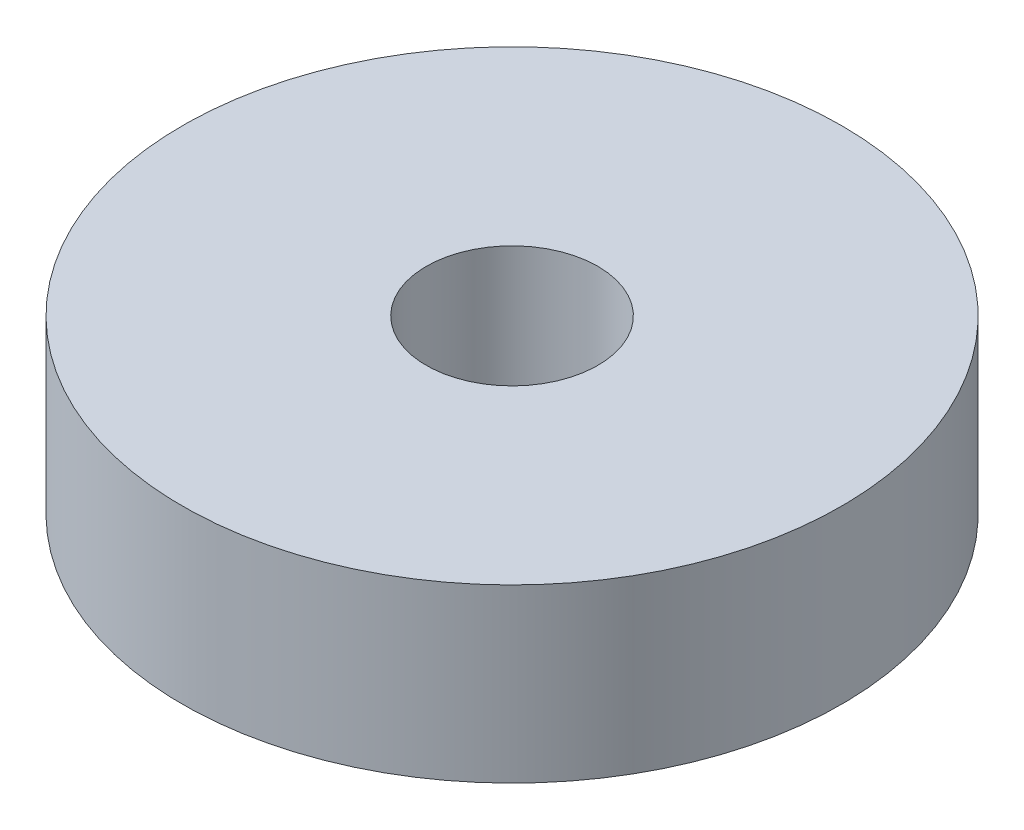
SolidWorks part; units mm, degrees
material "Ductile Iron"
ref_plane "Front Plane" through (0, 0, 0) normal (0, 0, 1) x (1, 0, 0)
ref_plane "Top Plane" through (0, 0, 0) normal (0, 1, 0) x (1, 0, 0)
ref_plane "Right Plane" through (0, 0, 0) normal (1, 0, 0) x (0, 0, -1)
sketch "Sketch1" plane through (0, 0, 0) normal (0, 0, 1) x (1, 0, 0)
  line L0 (0, 0) -> (0, 7801.7781) construction
  line L1 (0, 0) -> (7801.7781, 0) construction
  line L3 (6.096, 1.5875) -> (1.5875, 1.5875)
  line L4 (6.096, 1.5875) -> (6.096, -1.5875)
  line L5 (6.096, -1.5875) -> (1.5875, -1.5875)
  line L6 (1.5875, 1.5875) -> (1.5875, -1.5875)
  line L7 (6.096, 1.5875) -> (1.5875, -1.5875) construction
  line L8 (6.096, -1.5875) -> (1.5875, 1.5875) construction
  point P5 (3.8417, 0)
  dimension "D1" = 6.096
  dimension "D2" = 3.175
  dimension "D3" = 1.5875
revolve "Revolve1" add sketch "Sketch1" angle 360 about L0
